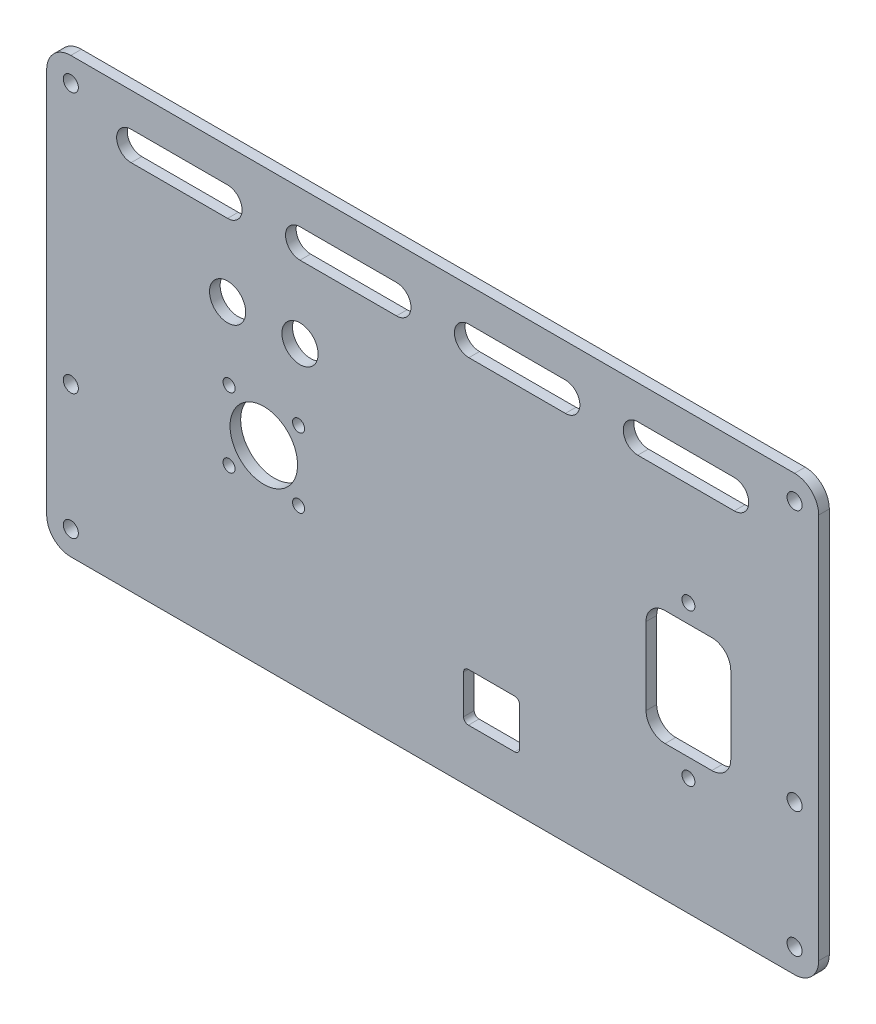
SolidWorks part; units mm, degrees
ref_plane "Front Plane" through (0, 0, 0) normal (0, 0, 1) x (1, 0, 0)
ref_plane "Top Plane" through (0, 0, 0) normal (0, 1, 0) x (1, 0, 0)
ref_plane "Right Plane" through (0, 0, 0) normal (1, 0, 0) x (0, 0, -1)
sketch "Sketch1" plane through (0, 0, 0) normal (0, 0, 1) x (1, 0, 0)
  line L1 (-101.6, -57.15) -> (101.6, -57.15)
  line L2 (-101.6, -57.15) -> (-101.6, 57.15)
  line L3 (-101.6, 57.15) -> (101.6, 57.15)
  line L4 (101.6, -57.15) -> (101.6, 57.15)
  line L5 (-101.6, -57.15) -> (101.6, 57.15) construction
  line L6 (-101.6, 57.15) -> (101.6, -57.15) construction
  point P0 (0, 0)
  dimension "D1" = 203.2
  dimension "D2" = 114.3
extrude "Boss-Extrude1" add sketch "Sketch1" along normal blind 2.794
hole_wizard "5/32 (0.15625) Diameter Hole1" positions "Sketch5" profile "Sketch6" hole size "5/32" standard "ANSI Inch" end condition through all
sketch "Sketch5" plane through (0, 0, 2.794) normal (0, 0, 1) x (1, 0, 0)
  line L0 (0, 0) -> (0, 22.4012) construction
  line L1 (0, 0) -> (78.0468, 0) construction
  line L2 (-95.25, -50.8) -> (-95.25, 17.0858) construction
  point P15 (-95.25, 50.8)
  point P19 (95.25, 50.8)
  point P21 (95.25, -50.8)
  point P22 (-95.25, -50.8)
  point P38 (-95.25, -17.78)
  point P42 (95.25, -17.78)
  dimension "D1" = 190.5
  dimension "D2" = 101.6
  dimension "D3" = 33.02
sketch "Sketch6" plane through (95.25, -17.78, 2.794) normal (1, 0, 0) x (0, -1, 0)
  line L0 (0, 0) -> (0, 2.794)
  line L1 (0, 2.794) -> (1.9844, 2.794)
  line L2 (1.9844, 2.794) -> (1.9844, 0)
  line L5 (1.9844, 0) -> (0, 0)
  line L11 (0, -6.35) -> (0, 107.95) construction
  dimension "Thru Hole Dia." = 3.9688
  dimension "Thru Hole Depth" = 2.794
fillet "Fillet2" radius 6.35 4 edges at (-101.6, -57.15, 1.397) (101.6, -57.15, 1.397) (101.6, 57.15, 1.397) (-101.6, 57.15, 1.397)
sketch "Sketch7" plane through (0, 0, 0) normal (0, 0, -1) x (-1, 0, 0)
  line L0 (95.25, -57.15) -> (-95.25, -57.15) construction
  line L1 (-22.86, -43.18) -> (-8.128, -43.18)
  line L2 (-22.86, -43.18) -> (-22.86, -30.48)
  line L4 (-8.128, -43.18) -> (-8.128, -30.48)
  line L5 (44.45, -6.35) -> (44.45, 28.0524) construction
  line L6 (-15.494, -43.18) -> (-15.494, 42.4404) construction
  line L7 (101.6, 50.8) -> (101.6, -50.8) construction
  line L14 (-101.6, -50.8) -> (-101.6, 50.8) construction
  line L22 (-8.128, -30.48) -> (-22.86, -30.48)
  line L27 (108.8104, -6.35) -> (30.0893, -6.35) construction
  circle A3 centre (44.45, -6.35) radius 8.89
  circle A4 centre (53.6, 2.8) radius 1.5875
  circle A5 centre (35.3, 2.8) radius 1.5875
  circle A6 centre (53.6, -15.5) radius 1.5875
  circle A7 centre (35.3, -15.5) radius 1.5875
  dimension "D1" = 3.175
  dimension "D6" = 57.15
  dimension "D8" = 17.78
  dimension "D2" = 86.106
  dimension "D3" = 14.732
  dimension "D4" = 13.97
  dimension "D5" = 12.7
  dimension "D7" = 50.8
  dimension "D9" = 18.3
  dimension "D10" = 18.3
extrude "Cut-Extrude1" cut sketch "Sketch7" against normal through all
fillet "Fillet3" radius 1.27 4 edges at (22.86, -43.18, 1.397) (8.128, -43.18, 1.397) (22.86, -30.48, 1.397) (8.128, -30.48, 1.397)
hole_wizard "3/8 (0.375) Diameter Hole1" positions "Sketch8" profile "Sketch9" hole size "3/8" standard "ANSI Inch" end condition up to next
sketch "Sketch8" plane through (0, 0, 0) normal (0, 0, -1) x (-1, 0, 0)
  line L2 (-101.6, -50.8) -> (-101.6, 50.8) construction
  line L3 (-95.25, 57.15) -> (95.25, 57.15) construction
  line L4 (34.925, 21.59) -> (-127.1019, 21.59) construction
  point P0 (53.975, 21.59)
  point P8 (34.925, 21.59)
  dimension "D1" = 19.05
  dimension "D2" = 136.525
  dimension "D3" = 35.56
sketch "Sketch9" plane through (-53.975, 21.59, 0) normal (1, 0, 0) x (0, 1, 0)
  line L0 (0, 0) -> (0, 2.794)
  line L1 (0, 2.794) -> (4.7625, 2.794)
  line L2 (4.7625, 2.794) -> (4.7625, 0)
  line L5 (4.7625, 0) -> (0, 0)
  line L11 (0, -6.35) -> (0, 107.95) construction
  dimension "Thru Hole Dia." = 9.525
  dimension "Thru Hole Depth" = 2.794
sketch "Sketch12" plane through (0, 0, 0) normal (0, 0, -1) x (-1, 0, 0)
  line L0 (-73.46, 8.8) -> (-61.16, 8.8)
  line L1 (-78.46, 3.8) -> (-78.46, -16.5)
  line L2 (-73.46, -21.5) -> (-61.16, -21.5)
  line L3 (-56.16, 3.8) -> (-56.16, -16.5)
  line L4 (-78.46, 8.8) -> (-56.16, -21.5) construction
  line L5 (-78.46, -21.5) -> (-56.16, 8.8) construction
  line L6 (-67.31, -6.35) -> (-69.2804, -6.35) construction
  line L7 (-67.31, -6.35) -> (-67.31, 31.4723) construction
  line L9 (-101.6, -50.8) -> (-101.6, 50.8) construction
  line L10 (95.25, -57.15) -> (-95.25, -57.15) construction
  circle A0 centre (-67.31, -26.35) radius 1.7
  circle A1 centre (-67.31, 13.65) radius 1.7
  arc A2 (-78.46, -16.5) -> (-73.46, -21.5) centre (-73.46, -16.5) ccw
  arc A3 (-61.16, -21.5) -> (-56.16, -16.5) centre (-61.16, -16.5) ccw
  arc A4 (-56.16, 3.8) -> (-61.16, 8.8) centre (-61.16, 3.8) ccw
  arc A5 (-73.46, 8.8) -> (-78.46, 3.8) centre (-73.46, 3.8) ccw
  point P0 (-67.31, -6.35)
  dimension "D1" = 5
  dimension "D7" = 3.4
  dimension "D2" = 22.3
  dimension "D3" = 30.3
  dimension "D4" = 40
  dimension "D5" = 34.29
  dimension "D6" = 50.8
extrude "Cut-Extrude4" cut sketch "Sketch12" against normal through all
sketch "Sketch13" plane through (0, 0, 0) normal (0, 0, -1) x (-1, 0, 0)
  line L0 (-79.375, 44.45) -> (-53.975, 44.45) construction
  line L1 (-79.375, 48.26) -> (-53.975, 48.26)
  line L2 (-79.375, 40.64) -> (-53.975, 40.64)
  line L3 (-101.6, -50.8) -> (-101.6, 50.8) construction
  line L4 (-95.25, 57.15) -> (95.25, 57.15) construction
  line L5 (-34.925, 44.45) -> (-9.525, 44.45) construction
  line L8 (0, 0) -> (0, 78.0178) construction
  line L9 (79.375, 44.45) -> (53.975, 44.45) construction
  line L10 (79.375, 48.26) -> (53.975, 48.26)
  line L11 (79.375, 40.64) -> (53.975, 40.64)
  line L12 (-34.925, 48.26) -> (-9.525, 48.26)
  line L13 (-34.925, 40.64) -> (-9.525, 40.64)
  line L14 (34.925, 44.45) -> (9.525, 44.45) construction
  line L15 (34.925, 48.26) -> (9.525, 48.26)
  line L16 (34.925, 40.64) -> (9.525, 40.64)
  arc A0 (-79.375, 48.26) -> (-79.375, 40.64) centre (-79.375, 44.45) ccw
  arc A1 (-53.975, 40.64) -> (-53.975, 48.26) centre (-53.975, 44.45) ccw
  arc A4 (79.375, 48.26) -> (79.375, 40.64) centre (79.375, 44.45) cw
  arc A5 (53.975, 40.64) -> (53.975, 48.26) centre (53.975, 44.45) cw
  arc A6 (-34.925, 48.26) -> (-34.925, 40.64) centre (-34.925, 44.45) ccw
  arc A7 (-9.525, 40.64) -> (-9.525, 48.26) centre (-9.525, 44.45) ccw
  arc A8 (34.925, 48.26) -> (34.925, 40.64) centre (34.925, 44.45) cw
  arc A9 (9.525, 40.64) -> (9.525, 48.26) centre (9.525, 44.45) cw
  point P2 (-66.675, 44.45)
  point P13 (-22.225, 44.45)
  point P22 (66.675, 44.45)
  point P29 (22.225, 44.45)
  dimension "D1" = 3.81
  dimension "D4" = 12.7
  dimension "D2" = 25.4
  dimension "D3" = 22.225
  dimension "D5" = 19.05
  dimension "D6" = 19.05
extrude "Cut-Extrude5" cut sketch "Sketch13" against normal through all
